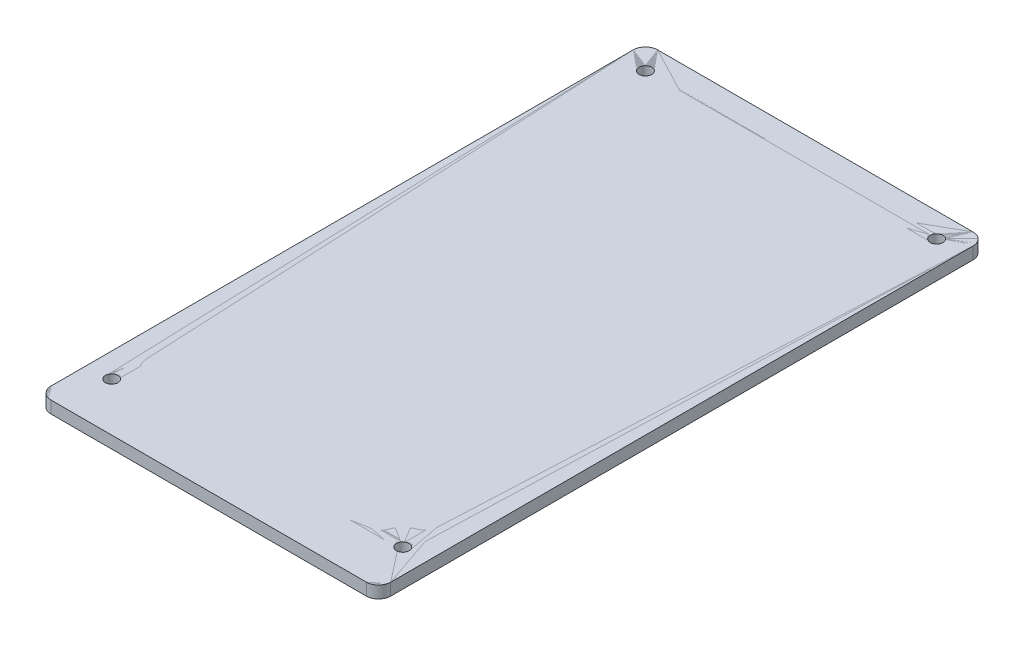
SolidWorks part; units mm, degrees
material "Balsa"
ref_plane "Front Plane" through (0, 0, 0) normal (0, 0, 1) x (1, 0, 0)
ref_plane "Top Plane" through (0, 0, 0) normal (0, 1, 0) x (1, 0, 0)
ref_plane "Right Plane" through (0, 0, 0) normal (1, 0, 0) x (0, 0, -1)
sketch "Sketch1" plane through (0, 0, 0) normal (0, 1, 0) x (1, 0, 0)
  line L1 (-88.9, 158.75) -> (88.9, 158.75)
  line L2 (-88.9, 158.75) -> (-88.9, -158.75)
  line L3 (-88.9, -158.75) -> (88.9, -158.75)
  line L4 (88.9, 158.75) -> (88.9, -158.75)
  line L5 (-88.9, 158.75) -> (88.9, -158.75) construction
  line L6 (-88.9, -158.75) -> (88.9, 158.75) construction
  point P0 (0, 0)
  dimension "D1" = 177.8
  dimension "D2" = 317.5
extrude "Base" add sketch "Sketch1" along normal blind 6.35
sketch "Sketch3" plane through (0, 0, 0) normal (0, -1, 0) x (1, 0, 0)
  line L5 (88.9, -158.75) -> (-88.9, -158.75) construction
  line L8 (-76.2, 133.35) -> (76.2, 133.35) construction
  line L9 (-76.2, 133.35) -> (-76.2, -146.05) construction
  line L10 (-76.2, -146.05) -> (76.2, -146.05) construction
  line L11 (76.2, 133.35) -> (76.2, -146.05) construction
  line L12 (0, -146.05) -> (0, 133.35) construction
  line L13 (-76.2, -6.35) -> (76.2, -6.35) construction
  line L14 (88.9, 158.75) -> (88.9, -158.75) construction
  line L15 (-88.9, 158.75) -> (88.9, 158.75) construction
  circle A4 centre (-76.2, -146.05) radius 3.302
  circle A5 centre (76.2, -146.05) radius 3.302
  circle A6 centre (76.2, 133.35) radius 3.302
  circle A7 centre (-76.2, 133.35) radius 3.302
  point P258 (0, -6.35)
  dimension "D3" = 6.604
  dimension "D1" = 12.7
  dimension "D2" = 12.7
  dimension "D4" = 25.4
extrude "Holes" cut sketch "Sketch3" against normal through all both and the other way through all
sketch "Sketch6" plane through (0, 0, 0) normal (0, -1, 0) x (1, 0, 0)
  line L5 (-76.2, 133.35) -> (-76.2, -146.05) construction
  line L6 (-76.2, 133.35) -> (76.2, 133.35) construction
  line L8 (0, -921.4775) -> (0, 49078.5225) construction
  line L10 (-963.0198, -6.35) -> (49036.9802, -6.35) construction
  line L12 (0, -146.05) -> (0, 133.35) construction
  line L13 (-76.2, -6.35) -> (76.2, -6.35) construction
  line L14 (-76.2, 120.65) -> (-76.2, -133.35)
  line L15 (-63.5, 133.35) -> (63.5, 133.35)
  line L16 (76.2, 120.65) -> (76.2, -133.35)
  line L17 (-63.5, -146.05) -> (63.5, -146.05)
  arc A0 (-76.2, 120.65) -> (-63.5, 133.35) centre (-76.2, 133.35) ccw
  arc A1 (76.2, 120.65) -> (63.5, 133.35) centre (76.2, 133.35) cw
  arc A2 (76.2, -133.35) -> (63.5, -146.05) centre (76.2, -146.05) ccw
  arc A3 (-76.2, -133.35) -> (-63.5, -146.05) centre (-76.2, -146.05) cw
  point P17 (0, -146.05)
  point P20 (-76.2, -6.35)
  point P24 (0, 133.35)
  point P31 (76.2, -6.35)
  dimension "D1" = 12.7
extrude "Inner Cutout" cut sketch "Sketch6" against normal through all both and the other way through all
fillet "Fillet1" radius 6.35 12 edges at (-88.9, 3.175, -158.75) (88.9, 3.175, -158.75) (88.9, 3.175, 158.75) (-88.9, 3.175, 158.75) (76.2, 3.175, 120.65) (63.5, 3.175, 133.35) (-63.5, 3.175, 133.35) (-76.2, 3.175, 120.65) (-76.2, 3.175, -133.35) (-63.5, 3.175, -146.05) (76.2, 3.175, -133.35) (63.5, 3.175, -146.05)
sketch "Sketch7" plane through (0, 6.35, 0) normal (0, 1, 0) x (1, 0, 0)
  line L4 (82.55, 158.75) -> (-82.55, 158.75)
  line L5 (-88.9, 152.4) -> (-88.9, -152.4)
  line L6 (-82.55, -158.75) -> (82.55, -158.75)
  line L7 (88.9, -152.4) -> (88.9, 152.4)
  line L8 (82.55, 158.75) -> (-82.55, 158.75)
  line L9 (-88.9, 152.4) -> (-88.9, -152.4)
  line L10 (-82.55, -158.75) -> (82.55, -158.75)
  line L11 (88.9, -152.4) -> (88.9, 152.4)
  circle A0 centre (-76.2, -133.35) radius 3.302 construction
  circle A1 centre (76.2, -133.35) radius 3.302 construction
  circle A2 centre (-76.2, 146.05) radius 3.302 construction
  circle A3 centre (76.2, 146.05) radius 3.302 construction
  arc A4 (-82.55, 158.75) -> (-88.9, 152.4) centre (-82.55, 152.4) ccw
  arc A5 (-88.9, -152.4) -> (-82.55, -158.75) centre (-82.55, -152.4) ccw
  arc A6 (82.55, -158.75) -> (88.9, -152.4) centre (82.55, -152.4) ccw
  arc A7 (88.9, 152.4) -> (82.55, 158.75) centre (82.55, 152.4) ccw
  arc A8 (-82.55, 158.75) -> (-88.9, 152.4) centre (-82.55, 152.4) ccw
  arc A9 (-88.9, -152.4) -> (-82.55, -158.75) centre (-82.55, -152.4) ccw
  arc A10 (82.55, -158.75) -> (88.9, -152.4) centre (82.55, -152.4) ccw
  arc A11 (88.9, 152.4) -> (82.55, 158.75) centre (82.55, 152.4) ccw
  circle A12 centre (-76.2, -133.35) radius 3.302
  circle A13 centre (76.2, -133.35) radius 3.302
  circle A14 centre (-76.2, 146.05) radius 3.302
  circle A15 centre (76.2, 146.05) radius 3.302
  dimension "D1" = 0
surface "Surface-Plane1" sketch "Sketch7"
sketch "Sketch8" plane through (0, 0, 0) normal (0, -1, 0) x (1, 0, 0)
  line L4 (88.9, -152.4) -> (88.9, 152.4)
  line L5 (82.55, 158.75) -> (-82.55, 158.75)
  line L6 (-88.9, 152.4) -> (-88.9, -152.4)
  line L7 (-82.55, -158.75) -> (82.55, -158.75)
  line L8 (88.9, -152.4) -> (88.9, 152.4)
  line L9 (82.55, 158.75) -> (-82.55, 158.75)
  line L10 (-88.9, 152.4) -> (-88.9, -152.4)
  line L11 (-82.55, -158.75) -> (82.55, -158.75)
  circle A1 centre (76.2, -146.05) radius 3.302
  circle A2 centre (76.2, -146.05) radius 3.302
  circle A3 centre (-76.2, -146.05) radius 3.302
  circle A4 centre (-76.2, -146.05) radius 3.302
  circle A5 centre (76.2, 133.35) radius 3.302
  circle A6 centre (76.2, 133.35) radius 3.302
  circle A7 centre (-76.2, 133.35) radius 3.302
  circle A8 centre (-76.2, 133.35) radius 3.302
  arc A12 (88.9, 152.4) -> (82.55, 158.75) centre (82.55, 152.4) ccw
  arc A13 (-82.55, 158.75) -> (-88.9, 152.4) centre (-82.55, 152.4) ccw
  arc A14 (-88.9, -152.4) -> (-82.55, -158.75) centre (-82.55, -152.4) ccw
  arc A15 (82.55, -158.75) -> (88.9, -152.4) centre (82.55, -152.4) ccw
  arc A16 (88.9, 152.4) -> (82.55, 158.75) centre (82.55, 152.4) ccw
  arc A17 (-82.55, 158.75) -> (-88.9, 152.4) centre (-82.55, 152.4) ccw
  arc A18 (-88.9, -152.4) -> (-82.55, -158.75) centre (-82.55, -152.4) ccw
  arc A19 (82.55, -158.75) -> (88.9, -152.4) centre (82.55, -152.4) ccw
  dimension "D1" = 0
  dimension "D2" = 0
  dimension "D3" = 0
  dimension "D4" = 0
  dimension "D5" = 0
surface "Surface-Plane2" sketch "Sketch8"
